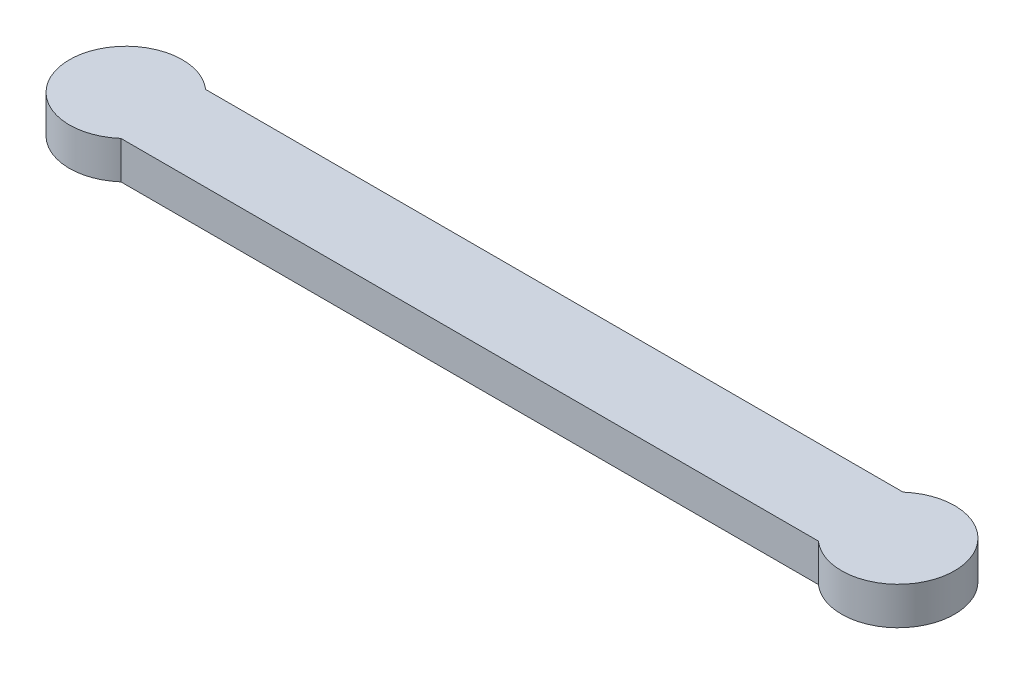
SolidWorks part; units mm, degrees
ref_plane "前视基准面" through (0, 0, 0) normal (0, 0, 1) x (1, 0, 0)
ref_plane "上视基准面" through (0, 0, 0) normal (0, 1, 0) x (1, 0, 0)
ref_plane "右视基准面" through (0, 0, 0) normal (1, 0, 0) x (0, 0, -1)
sketch "草图1" plane through (0, 0, 0) normal (0, 1, 0) x (1, 0, 0)
  line L0 (0, 0) -> (82, 0) construction
  line L1 (0, 4.5) -> (82, 4.5)
  line L2 (0, -4.5) -> (82, -4.5)
  arc A0 (0, 4.5) -> (0, -4.5) centre (0, 0) ccw
  arc A1 (82, -4.5) -> (82, 4.5) centre (82, 0) ccw
  circle A2 centre (0, 0) radius 6
  circle A3 centre (82, 0) radius 6
  point P3 (41, 0)
  dimension "D2" = 4.5
  dimension "D3" = 12
  dimension "D1" = 82
extrude "凸台-拉伸1" add sketch "草图1" along normal blind 4
